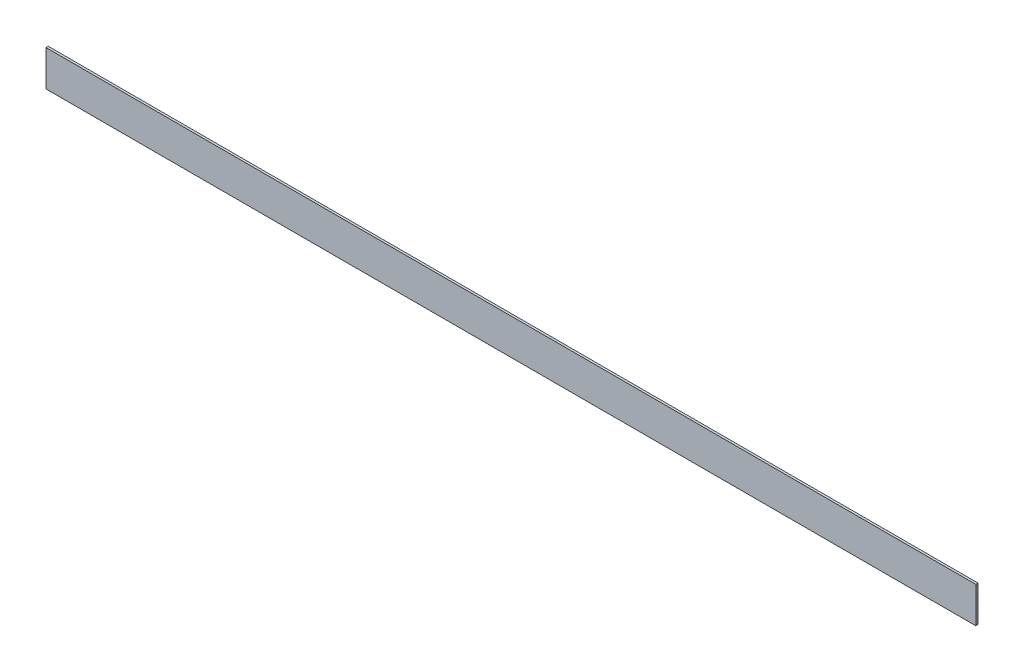
SolidWorks part; units mm, degrees
ref_plane "Front Plane" through (0, 0, 0) normal (0, 0, 1) x (1, 0, 0)
ref_plane "Top Plane" through (0, 0, 0) normal (0, 1, 0) x (1, 0, 0)
ref_plane "Right Plane" through (0, 0, 0) normal (1, 0, 0) x (0, 0, -1)
sketch "Sketch1" plane through (0, 0, 0) normal (0, 0, 1) x (1, 0, 0)
  line L1 (-48.1163, 14.2105) -> (478.4257, 14.2105)
  line L2 (-48.1163, 14.2105) -> (-48.1163, -6.1095)
  line L3 (-48.1163, -6.1095) -> (478.4257, -6.1095)
  line L4 (478.4257, 14.2105) -> (478.4257, -6.1095)
  dimension "D1" = 526.542
  dimension "D2" = 20.32
extrude "Boss-Extrude1" add sketch "Sketch1" along normal blind 1.27
